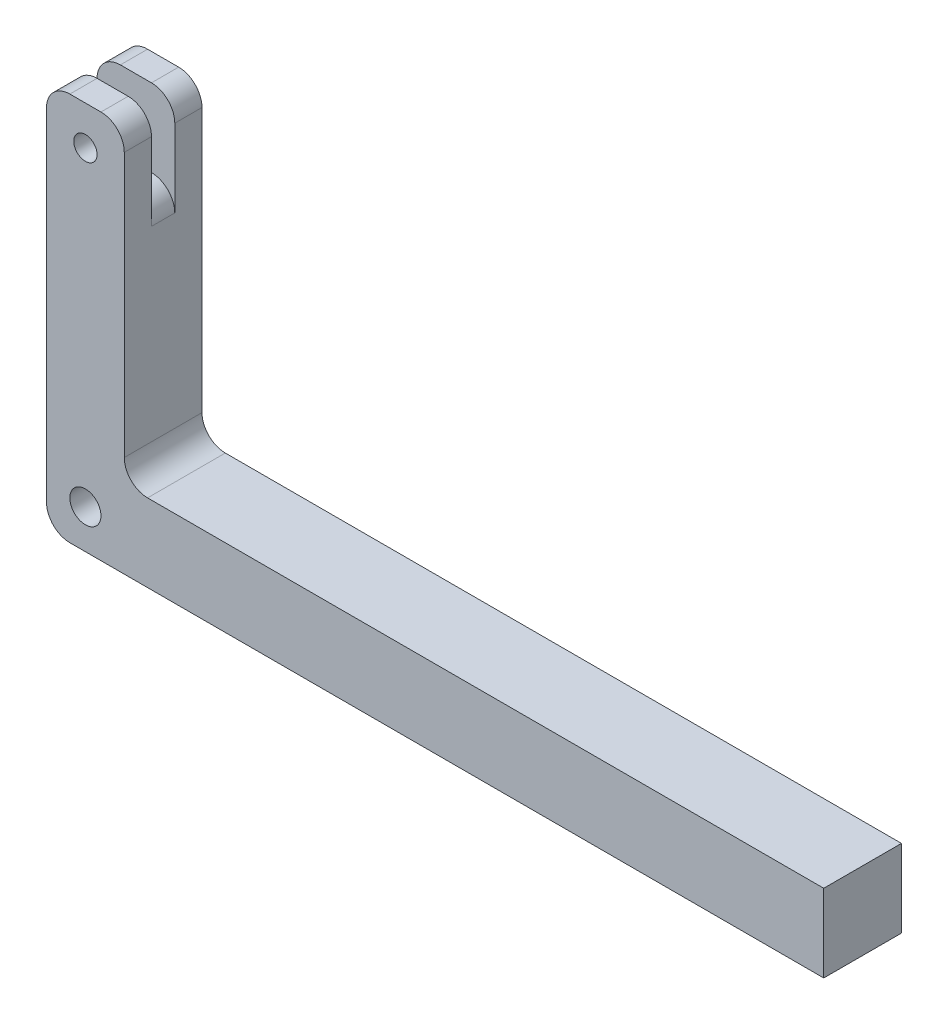
SolidWorks part; units mm, degrees
ref_plane "Front Plane" through (0, 0, 0) normal (0, 0, 1) x (1, 0, 0)
ref_plane "Top Plane" through (0, 0, 0) normal (0, 1, 0) x (1, 0, 0)
ref_plane "Right Plane" through (0, 0, 0) normal (1, 0, 0) x (0, 0, -1)
sketch "Sketch1" plane through (0, 0, 0) normal (0, 0, 1) x (1, 0, 0)
  line L0 (0, 0) -> (100, 0)
  line L1 (100, 0) -> (100, 10)
  line L2 (100, 10) -> (10, 10)
  line L3 (10, 10) -> (10, 50)
  line L4 (10, 50) -> (0, 50)
  line L5 (0, 50) -> (0, 0)
  circle A0 centre (5, 5) radius 2
  point P9 (5, 50)
  point P10 (0, 0)
  point P11 (100, 5)
  dimension "D4" = 4
  dimension "D1" = 50
  dimension "D2" = 100
  dimension "D3" = 10
extrude "Boss-Extrude1" add sketch "Sketch1" along normal blind 10
sketch "Sketch2" plane through (0, 50, 0) normal (0, 1, 0) x (1, 0, 0)
  line L5 (0, -10) -> (0, 0) construction
  line L6 (0, -6.5) -> (10, -6.5)
  line L7 (0, -6.5) -> (0, -3.5)
  line L9 (0, -3.5) -> (10, -3.5)
  line L10 (10, -6.5) -> (10, -3.5)
  line L11 (10, -10) -> (10, 0) construction
  point P9 (0, -5)
  point P10 (10, -5)
  dimension "D1" = 3
extrude "Cut-Extrude1" cut sketch "Sketch2" against normal blind 10
hole_wizard "Ø3.0mm Dowel Hole1" positions "Sketch3" profile "Sketch5" hole size "Ø3.0" standard "ANSI Metric"
sketch "Sketch3" plane through (0, 0, 0) normal (0, 0, 1) x (1, 0, 0)
  line L1 (0, 45) -> (10, 45) construction
  line L2 (0, 50) -> (0, 0) construction
  line L3 (10, 10) -> (10, 50) construction
  line L5 (5, 45) -> (5, 50) construction
  line L6 (10, 50) -> (0, 50) construction
  point P0 (5, 45)
  point P19 (5, 45)
  dimension "D1" = 5
sketch "Sketch5" plane through (5, 45, 0) normal (1, 0, 0) x (0, 1, 0)
  line L0 (0, 0) -> (0, 10.9003)
  line L1 (0, 10.9003) -> (1.5, 9.999)
  line L2 (1.5, 9.999) -> (1.5, 0)
  line L5 (1.5, 0) -> (0, 0)
  line L10 (0, 10.9003) -> (-1.5, 9.999) construction
  line L11 (0, -6.35) -> (0, 107.95) construction
  dimension "Hole Dia." = 3
  dimension "Hole Depth" = 9.999
  dimension "Drill Angle" = 118
fillet "Fillet2" radius 3 8 edges at (10, 40, 5) (10, 50, 1.75) (10, 50, 8.25) (0, 50, 8.25) (0, 40, 5) (0, 50, 1.75) (10, 10, 5) (0, 0, 5)
